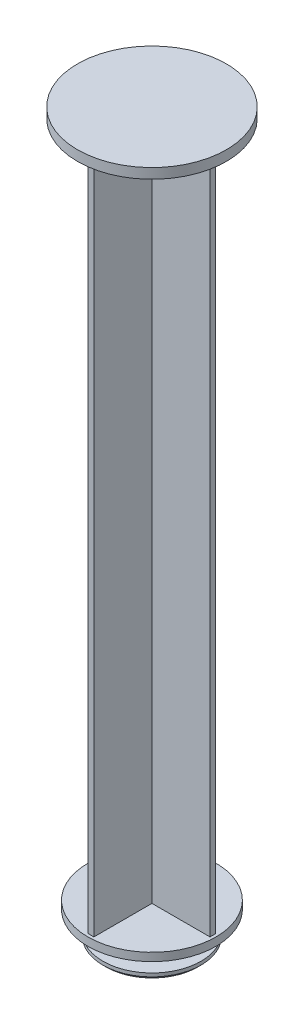
SolidWorks part; units mm, degrees
ref_plane "Front Plane" through (0, 0, 0) normal (0, 0, 1) x (1, 0, 0)
ref_plane "Top Plane" through (0, 0, 0) normal (0, 1, 0) x (1, 0, 0)
ref_plane "Right Plane" through (0, 0, 0) normal (1, 0, 0) x (0, 0, -1)
sketch "Sketch1" plane through (0, 0, 0) normal (0, 1, 0) x (1, 0, 0)
  circle A0 centre (0, 0) radius 7.25
  dimension "D1" = 14.5
extrude "Boss-Extrude1" add sketch "Sketch1" along normal blind 1
chamfer "Chamfer1" distance 0.5 angle 45 1 edges at (0, 0, 7.25)
sketch "Sketch2" plane through (0, 1, 0) normal (0, 1, 0) x (1, 0, 0)
  line L0 (-0.6, 5.5) -> (-0.6, -5.5)
  line L1 (-0.6, 5.5) -> (0.6, 5.5)
  line L2 (-0.6, -5.5) -> (0.6, -5.5)
  line L3 (0.6, 5.5) -> (0.6, -5.5)
  line L4 (-0.6, 5.5) -> (0.6, -5.5) construction
  line L5 (-0.6, -5.5) -> (0.6, 5.5) construction
  point P1 (0, 0)
  dimension "D1" = 1.2
  dimension "D2" = 11
extrude "Boss-Extrude2" add sketch "Sketch2" along normal blind 3
sketch "Sketch3" plane through (0, 4, 0) normal (0, 1, 0) x (1, 0, 0)
  circle A0 centre (0, 0) radius 9.45
  dimension "D1" = 18.9
extrude "Boss-Extrude3" add sketch "Sketch3" along normal blind 1.2
sketch "Sketch4" plane through (0, 5.2, 0) normal (0, 1, 0) x (1, 0, 0)
  line L1 (-0.425, 9) -> (0.425, 9)
  line L2 (-0.425, 9) -> (-0.425, -9)
  line L3 (-0.425, -9) -> (0.425, -9)
  line L4 (0.425, 9) -> (0.425, -9)
  line L5 (-0.425, 9) -> (0.425, -9) construction
  line L6 (-0.425, -9) -> (0.425, 9) construction
  point P0 (0, 0)
  dimension "D1" = 0.85
  dimension "D2" = 18
extrude "Boss-Extrude4" add sketch "Sketch4" along normal blind 100
pattern_circular "CirPattern2" count 2 over 90 about axis through (0, 0, 0) along (0, 1, 0) of "Boss-Extrude2", "Boss-Extrude4"
sketch "Sketch6" plane through (0, 105.2, 0) normal (0, 1, 0) x (1, 0, 0)
  circle A0 centre (0, 0) radius 11
  dimension "D1" = 22
extrude "Boss-Extrude5" add sketch "Sketch6" along normal blind 1.5
